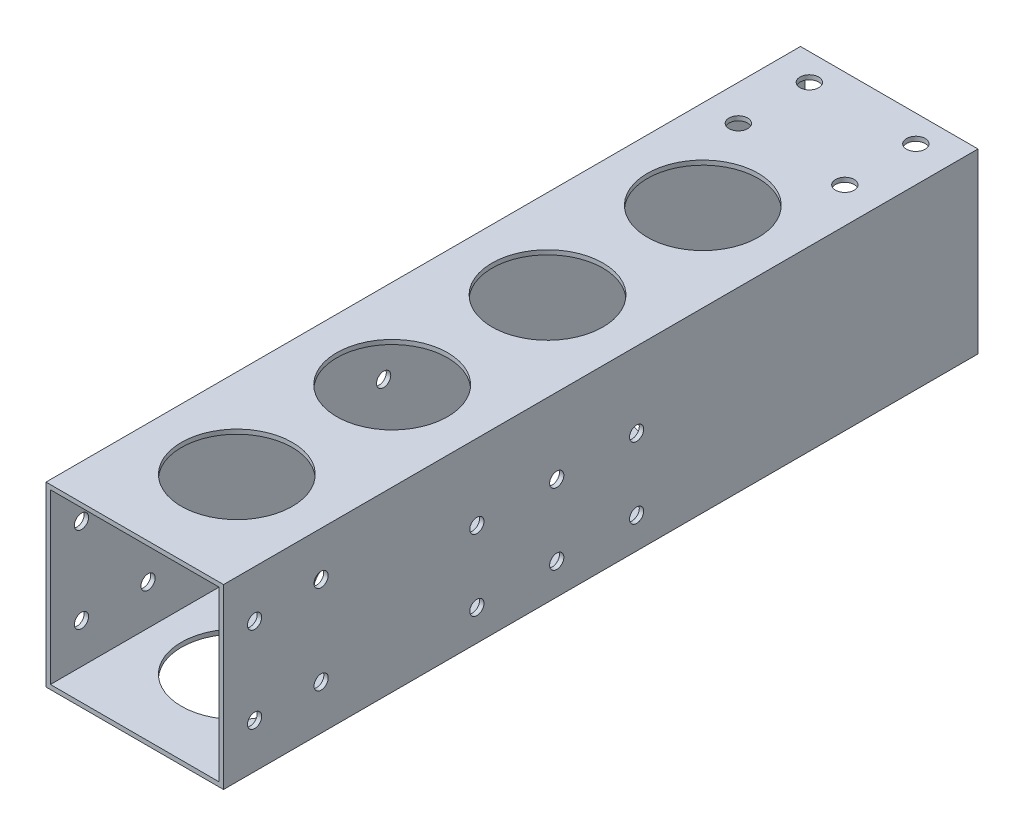
SolidWorks part; units mm, degrees
material "1060-H18 棒材(SS)"
ref_plane "前视基准面" through (0, 0, 0) normal (0, 0, 1) x (1, 0, 0)
ref_plane "上视基准面" through (0, 0, 0) normal (0, 1, 0) x (1, 0, 0)
ref_plane "右视基准面" through (0, 0, 0) normal (1, 0, 0) x (0, 0, -1)
other "Configuration Table"
sketch "草图1" plane through (0, 0, 0) normal (0, 0, 1) x (1, 0, 0)
  line L1 (0, 0) -> (40, 0)
  line L2 (0, 0) -> (0, 40)
  line L3 (0, 40) -> (40, 40)
  line L4 (40, 0) -> (40, 40)
  line L5 (1, 1) -> (39, 1)
  line L6 (1, 1) -> (1, 39)
  line L7 (1, 39) -> (39, 39)
  line L8 (39, 1) -> (39, 39)
  dimension "D1" = 40
  dimension "D2" = 40
  dimension "D3" = 1
  dimension "D4" = 1
  dimension "D5" = 1
  dimension "D6" = 1
extrude "凸台-拉伸1" add sketch "草图1" along normal blind 170
sketch "草图2" plane through (0, 0, 0) normal (0, -1, 0) x (1, 0, 0)
  circle A1 centre (8, 6) radius 2.1
  circle A2 centre (8, 6) radius 2.1
  circle A3 centre (32, 22) radius 2.1
  circle A4 centre (32, 22) radius 2.1
  circle A5 centre (8, 22) radius 2.1
  circle A6 centre (8, 22) radius 2.1
  circle A7 centre (72, -7) radius 2.1
  circle A8 centre (72, -7) radius 2.1 construction
  circle A9 centre (60, -7) radius 2.1
  circle A10 centre (60, -7) radius 2.1 construction
  circle A11 centre (-20, -7) radius 2.1
  circle A12 centre (-20, -7) radius 2.1 construction
  circle A13 centre (-32, -7) radius 2.1
  circle A14 centre (-32, -7) radius 2.1 construction
  circle A15 centre (32, 6) radius 2.1
  circle A16 centre (32, 6) radius 2.1
  dimension "D1" = 0
  dimension "D2" = 0
  dimension "D3" = 0
  dimension "D4" = 0
  dimension "D5" = 0
  dimension "D6" = 0
  dimension "D7" = 0
  dimension "D8" = 0
extrude "切除-拉伸1" cut sketch "草图2" against normal through all
sketch "草图12" plane through (0, 0, 0) normal (-1, 0, 0) x (0, 0, 1)
  line L0 (170, 40) -> (170, 0) construction
  line L1 (170, 0) -> (0, 0) construction
  line L2 (112.92, 23) -> (112.92, 7) construction
  line L3 (112.92, 7) -> (94.92, 7) construction
  circle A0 centre (112.92, 7) radius 1.6
  circle A1 centre (94.92, 7) radius 1.6
  circle A2 centre (76.92, 7) radius 1.6
  circle A3 centre (94.92, 23) radius 1.6
  circle A4 centre (76.92, 23) radius 1.6
  circle A5 centre (112.92, 23) radius 1.6
  dimension "D3" = 3.2
  dimension "D4" = 3
  dimension "D1" = 57.08
  dimension "D2" = 7
  dimension "D6" = 16
  dimension "D7" = 18
  dimension "D8" = 90
  dimension "D5" = 2
extrude "切除-拉伸2" cut sketch "草图12" against normal through all
sketch "草图13" plane through (0, 0, 0) normal (-1, 0, 0) x (0, 0, 1)
  line L0 (170, 40) -> (170, 0) construction
  line L1 (170, 0) -> (0, 0) construction
  circle A0 centre (163, 29.3431) radius 1.6
  circle A1 centre (163, 10) radius 1.6
  circle A2 centre (148.0144, 30) radius 1.6
  circle A3 centre (148, 10) radius 1.6
  dimension "D5" = 3.2
  dimension "D1" = 7
  dimension "D2" = 7
  dimension "D3" = 29.3431
  dimension "D4" = 10
  dimension "D6" = 15
  dimension "D7" = 15
  dimension "D8" = 30
  dimension "D9" = 10
extrude "切除-拉伸3" cut sketch "草图13" against normal through all
sketch "草图14" plane through (0, 0, 0) normal (0, -1, 0) x (1, 0, 0)
  line L0 (40, 170) -> (40, 0) construction
  line L1 (0, 0) -> (40, 0) construction
  circle A0 centre (20, 42) radius 12.5
  circle A1 centre (20, 77) radius 12.5
  circle A2 centre (20, 112) radius 12.5
  circle A3 centre (20, 147) radius 12.5
  dimension "D2" = 25
  dimension "D1" = 20
  dimension "D3" = 42
  dimension "D5" = 35
  dimension "D4" = 4
extrude "切除-拉伸4" cut sketch "草图14" against normal through all
